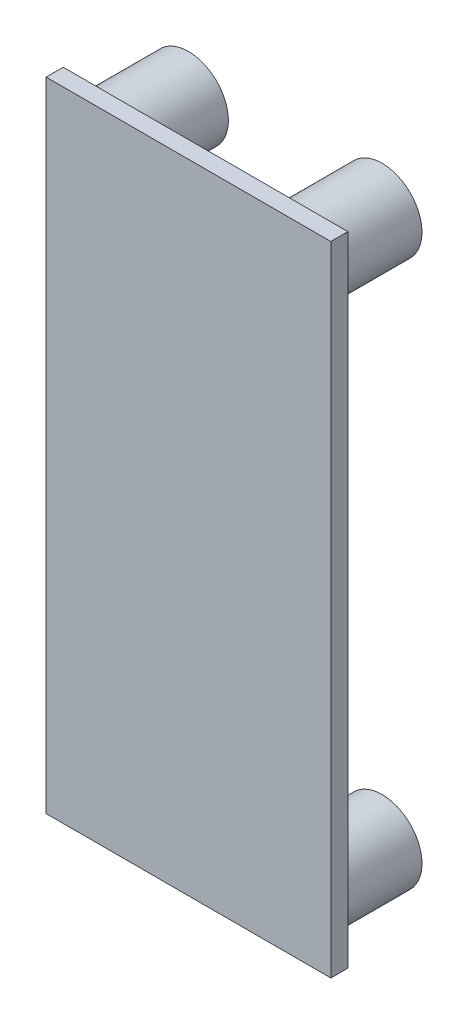
SolidWorks part; units mm, degrees
ref_plane "Спереди" through (0, 0, 0) normal (0, 0, 1) x (1, 0, 0)
ref_plane "Сверху" through (0, 0, 0) normal (0, 1, 0) x (1, 0, 0)
ref_plane "Справа" through (0, 0, 0) normal (1, 0, 0) x (0, 0, -1)
sketch "Эскиз1" plane through (0, 0, 0) normal (0, 0, 1) x (1, 0, 0)
  line L1 (0, 0) -> (25, 0)
  line L2 (0, 0) -> (0, 56)
  line L3 (0, 56) -> (25, 56)
  line L4 (25, 0) -> (25, 56)
  dimension "D1" = 56
  dimension "D2" = 25
extrude "Бобышка-Вытянуть1" add sketch "Эскиз1" along normal blind 1.5
sketch "Эскиз2" plane through (0, 0, 0) normal (0, 0, -1) x (-1, 0, 0)
  line L0 (-21, 52.2) -> (-21, 4.2) construction
  line L1 (-4, 52.2) -> (-4, 4.2) construction
  line L2 (-21, 52.2) -> (-4, 52.2) construction
  line L3 (-21, 4.2) -> (-4, 4.2) construction
  line L4 (-4, 52.2) -> (-4, 56) construction
  line L5 (-25, 56) -> (0, 56) construction
  line L6 (-4, 56) -> (-4, 52.2) construction
  line L7 (-4, 52.2) -> (0, 52.2) construction
  line L8 (0, 56) -> (0, 0) construction
  circle A0 centre (-21, 4.2) radius 1.5
  circle A1 centre (-4, 4.2) radius 1.5
  circle A2 centre (-4, 52.2) radius 1.5
  circle A3 centre (-21, 52.2) radius 1.5
  circle A4 centre (-21, 52.2) radius 3.5
  circle A5 centre (-4, 52.2) radius 3.5
  circle A6 centre (-21, 4.2) radius 3.5
  circle A7 centre (-4, 4.2) radius 3.5
  dimension "D1" = 3
  dimension "D6" = 7
  dimension "D2" = 48
  dimension "D3" = 17
  dimension "D4" = 3.8
  dimension "D5" = 4
extrude "Бобышка-Вытянуть2" add sketch "Эскиз2" along normal blind 7
